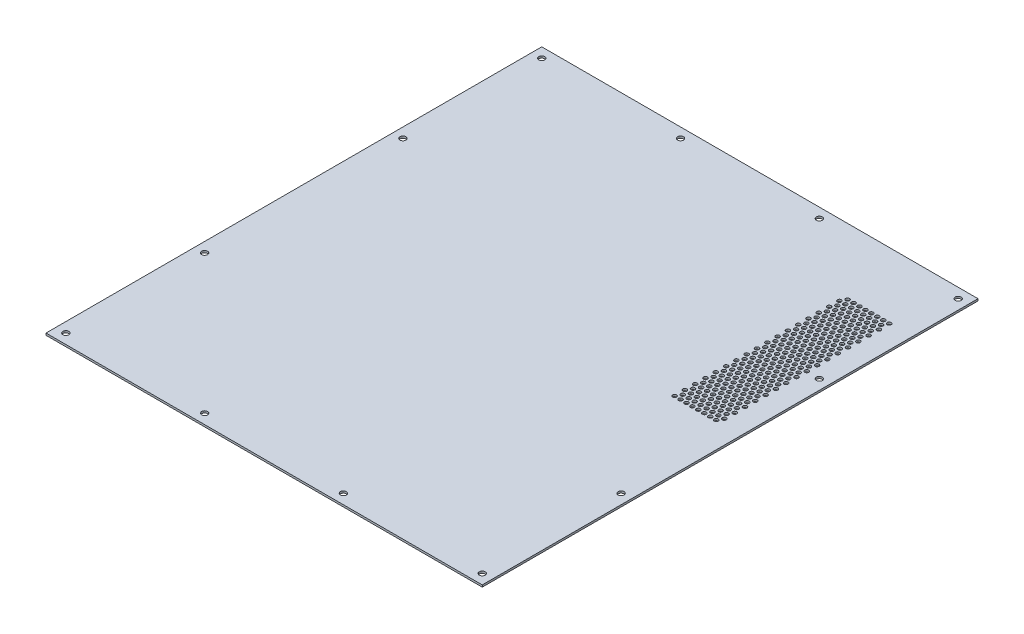
SolidWorks part; units mm, degrees
ref_plane "Front Plane" through (0, 0, 0) normal (0, 0, 1) x (1, 0, 0)
ref_plane "Top Plane" through (0, 0, 0) normal (0, 1, 0) x (1, 0, 0)
ref_plane "Right Plane" through (0, 0, 0) normal (1, 0, 0) x (0, 0, -1)
sketch "Sketch1" plane through (0, 0, 0) normal (0, 1, 0) x (1, 0, 0)
  line L0 (20, 20) -> (20, 480) construction
  line L1 (0, 0) -> (440, 0)
  line L2 (0, 0) -> (0, 500)
  line L3 (0, 500) -> (440, 500)
  line L4 (440, 0) -> (440, 500)
  line L5 (20, 480) -> (420, 480) construction
  line L6 (420, 20) -> (420, 480) construction
  line L7 (20, 20) -> (420, 20) construction
  line L9 (420, 440) -> (370, 440) construction
  line L10 (420, 440) -> (420, 260) construction
  line L11 (420, 260) -> (370, 260) construction
  line L12 (370, 440) -> (370, 260) construction
  circle A0 centre (372, 262) radius 2
  circle A1 centre (375, 267.1962) radius 2
  circle A2 centre (381, 267.1962) radius 2
  circle A3 centre (378, 262) radius 2
  circle A4 centre (387, 267.1962) radius 2
  circle A5 centre (384, 262) radius 2
  circle A6 centre (393, 267.1962) radius 2
  circle A7 centre (390, 262) radius 2
  circle A8 centre (399, 267.1962) radius 2
  circle A9 centre (396, 262) radius 2
  circle A10 centre (405, 267.1962) radius 2
  circle A11 centre (402, 262) radius 2
  circle A12 centre (411, 267.1962) radius 2
  circle A13 centre (408, 262) radius 2
  circle A14 centre (417, 267.1962) radius 2
  circle A15 centre (414, 262) radius 2
  circle A16 centre (381, 277.5862) radius 2
  circle A17 centre (378, 272.39) radius 2
  circle A18 centre (387, 277.5862) radius 2
  circle A19 centre (384, 272.39) radius 2
  circle A20 centre (393, 277.5862) radius 2
  circle A21 centre (390, 272.39) radius 2
  circle A22 centre (399, 277.5862) radius 2
  circle A23 centre (396, 272.39) radius 2
  circle A24 centre (405, 277.5862) radius 2
  circle A25 centre (402, 272.39) radius 2
  circle A26 centre (411, 277.5862) radius 2
  circle A27 centre (408, 272.39) radius 2
  circle A28 centre (417, 277.5862) radius 2
  circle A29 centre (414, 272.39) radius 2
  circle A30 centre (381, 287.9762) radius 2
  circle A31 centre (378, 282.78) radius 2
  circle A32 centre (387, 287.9762) radius 2
  circle A33 centre (384, 282.78) radius 2
  circle A34 centre (393, 287.9762) radius 2
  circle A35 centre (390, 282.78) radius 2
  circle A36 centre (399, 287.9762) radius 2
  circle A37 centre (396, 282.78) radius 2
  circle A38 centre (405, 287.9762) radius 2
  circle A39 centre (402, 282.78) radius 2
  circle A40 centre (411, 287.9762) radius 2
  circle A41 centre (408, 282.78) radius 2
  circle A42 centre (417, 287.9762) radius 2
  circle A43 centre (414, 282.78) radius 2
  circle A44 centre (381, 298.3662) radius 2
  circle A45 centre (378, 293.17) radius 2
  circle A46 centre (387, 298.3662) radius 2
  circle A47 centre (384, 293.17) radius 2
  circle A48 centre (393, 298.3662) radius 2
  circle A49 centre (390, 293.17) radius 2
  circle A50 centre (399, 298.3662) radius 2
  circle A51 centre (396, 293.17) radius 2
  circle A52 centre (405, 298.3662) radius 2
  circle A53 centre (402, 293.17) radius 2
  circle A54 centre (411, 298.3662) radius 2
  circle A55 centre (408, 293.17) radius 2
  circle A56 centre (417, 298.3662) radius 2
  circle A57 centre (414, 293.17) radius 2
  circle A58 centre (381, 308.7562) radius 2
  circle A59 centre (378, 303.56) radius 2
  circle A60 centre (387, 308.7562) radius 2
  circle A61 centre (384, 303.56) radius 2
  circle A62 centre (393, 308.7562) radius 2
  circle A63 centre (390, 303.56) radius 2
  circle A64 centre (399, 308.7562) radius 2
  circle A65 centre (396, 303.56) radius 2
  circle A66 centre (405, 308.7562) radius 2
  circle A67 centre (402, 303.56) radius 2
  circle A68 centre (411, 308.7562) radius 2
  circle A69 centre (408, 303.56) radius 2
  circle A70 centre (417, 308.7562) radius 2
  circle A71 centre (414, 303.56) radius 2
  circle A72 centre (381, 319.1462) radius 2
  circle A73 centre (378, 313.95) radius 2
  circle A74 centre (387, 319.1462) radius 2
  circle A75 centre (384, 313.95) radius 2
  circle A76 centre (393, 319.1462) radius 2
  circle A77 centre (390, 313.95) radius 2
  circle A78 centre (399, 319.1462) radius 2
  circle A79 centre (396, 313.95) radius 2
  circle A80 centre (405, 319.1462) radius 2
  circle A81 centre (402, 313.95) radius 2
  circle A82 centre (411, 319.1462) radius 2
  circle A83 centre (408, 313.95) radius 2
  circle A84 centre (417, 319.1462) radius 2
  circle A85 centre (414, 313.95) radius 2
  circle A86 centre (381, 329.5362) radius 2
  circle A87 centre (378, 324.34) radius 2
  circle A88 centre (387, 329.5362) radius 2
  circle A89 centre (384, 324.34) radius 2
  circle A90 centre (393, 329.5362) radius 2
  circle A91 centre (390, 324.34) radius 2
  circle A92 centre (399, 329.5362) radius 2
  circle A93 centre (396, 324.34) radius 2
  circle A94 centre (405, 329.5362) radius 2
  circle A95 centre (402, 324.34) radius 2
  circle A96 centre (411, 329.5362) radius 2
  circle A97 centre (408, 324.34) radius 2
  circle A98 centre (417, 329.5362) radius 2
  circle A99 centre (414, 324.34) radius 2
  circle A100 centre (381, 339.9262) radius 2
  circle A101 centre (378, 334.73) radius 2
  circle A102 centre (387, 339.9262) radius 2
  circle A103 centre (384, 334.73) radius 2
  circle A104 centre (393, 339.9262) radius 2
  circle A105 centre (390, 334.73) radius 2
  circle A106 centre (399, 339.9262) radius 2
  circle A107 centre (396, 334.73) radius 2
  circle A108 centre (405, 339.9262) radius 2
  circle A109 centre (402, 334.73) radius 2
  circle A110 centre (411, 339.9262) radius 2
  circle A111 centre (408, 334.73) radius 2
  circle A112 centre (417, 339.9262) radius 2
  circle A113 centre (414, 334.73) radius 2
  circle A114 centre (381, 350.3162) radius 2
  circle A115 centre (378, 345.12) radius 2
  circle A116 centre (387, 350.3162) radius 2
  circle A117 centre (384, 345.12) radius 2
  circle A118 centre (393, 350.3162) radius 2
  circle A119 centre (390, 345.12) radius 2
  circle A120 centre (399, 350.3162) radius 2
  circle A121 centre (396, 345.12) radius 2
  circle A122 centre (405, 350.3162) radius 2
  circle A123 centre (402, 345.12) radius 2
  circle A124 centre (411, 350.3162) radius 2
  circle A125 centre (408, 345.12) radius 2
  circle A126 centre (417, 350.3162) radius 2
  circle A127 centre (414, 345.12) radius 2
  circle A128 centre (381, 360.7062) radius 2
  circle A129 centre (378, 355.51) radius 2
  circle A130 centre (387, 360.7062) radius 2
  circle A131 centre (384, 355.51) radius 2
  circle A132 centre (393, 360.7062) radius 2
  circle A133 centre (390, 355.51) radius 2
  circle A134 centre (399, 360.7062) radius 2
  circle A135 centre (396, 355.51) radius 2
  circle A136 centre (405, 360.7062) radius 2
  circle A137 centre (402, 355.51) radius 2
  circle A138 centre (411, 360.7062) radius 2
  circle A139 centre (408, 355.51) radius 2
  circle A140 centre (417, 360.7062) radius 2
  circle A141 centre (414, 355.51) radius 2
  circle A142 centre (381, 371.0962) radius 2
  circle A143 centre (378, 365.9) radius 2
  circle A144 centre (387, 371.0962) radius 2
  circle A145 centre (384, 365.9) radius 2
  circle A146 centre (393, 371.0962) radius 2
  circle A147 centre (390, 365.9) radius 2
  circle A148 centre (399, 371.0962) radius 2
  circle A149 centre (396, 365.9) radius 2
  circle A150 centre (405, 371.0962) radius 2
  circle A151 centre (402, 365.9) radius 2
  circle A152 centre (411, 371.0962) radius 2
  circle A153 centre (408, 365.9) radius 2
  circle A154 centre (417, 371.0962) radius 2
  circle A155 centre (414, 365.9) radius 2
  circle A156 centre (381, 381.4862) radius 2
  circle A157 centre (378, 376.29) radius 2
  circle A158 centre (387, 381.4862) radius 2
  circle A159 centre (384, 376.29) radius 2
  circle A160 centre (393, 381.4862) radius 2
  circle A161 centre (390, 376.29) radius 2
  circle A162 centre (399, 381.4862) radius 2
  circle A163 centre (396, 376.29) radius 2
  circle A164 centre (405, 381.4862) radius 2
  circle A165 centre (402, 376.29) radius 2
  circle A166 centre (411, 381.4862) radius 2
  circle A167 centre (408, 376.29) radius 2
  circle A168 centre (417, 381.4862) radius 2
  circle A169 centre (414, 376.29) radius 2
  circle A170 centre (381, 391.8762) radius 2
  circle A171 centre (378, 386.68) radius 2
  circle A172 centre (387, 391.8762) radius 2
  circle A173 centre (384, 386.68) radius 2
  circle A174 centre (393, 391.8762) radius 2
  circle A175 centre (390, 386.68) radius 2
  circle A176 centre (399, 391.8762) radius 2
  circle A177 centre (396, 386.68) radius 2
  circle A178 centre (405, 391.8762) radius 2
  circle A179 centre (402, 386.68) radius 2
  circle A180 centre (411, 391.8762) radius 2
  circle A181 centre (408, 386.68) radius 2
  circle A182 centre (417, 391.8762) radius 2
  circle A183 centre (414, 386.68) radius 2
  circle A184 centre (381, 402.2662) radius 2
  circle A185 centre (378, 397.07) radius 2
  circle A186 centre (387, 402.2662) radius 2
  circle A187 centre (384, 397.07) radius 2
  circle A188 centre (393, 402.2662) radius 2
  circle A189 centre (390, 397.07) radius 2
  circle A190 centre (399, 402.2662) radius 2
  circle A191 centre (396, 397.07) radius 2
  circle A192 centre (405, 402.2662) radius 2
  circle A193 centre (402, 397.07) radius 2
  circle A194 centre (411, 402.2662) radius 2
  circle A195 centre (408, 397.07) radius 2
  circle A196 centre (417, 402.2662) radius 2
  circle A197 centre (414, 397.07) radius 2
  circle A198 centre (381, 412.6562) radius 2
  circle A199 centre (378, 407.46) radius 2
  circle A200 centre (387, 412.6562) radius 2
  circle A201 centre (384, 407.46) radius 2
  circle A202 centre (393, 412.6562) radius 2
  circle A203 centre (390, 407.46) radius 2
  circle A204 centre (399, 412.6562) radius 2
  circle A205 centre (396, 407.46) radius 2
  circle A206 centre (405, 412.6562) radius 2
  circle A207 centre (402, 407.46) radius 2
  circle A208 centre (411, 412.6562) radius 2
  circle A209 centre (408, 407.46) radius 2
  circle A210 centre (417, 412.6562) radius 2
  circle A211 centre (414, 407.46) radius 2
  circle A212 centre (381, 423.0462) radius 2
  circle A213 centre (378, 417.85) radius 2
  circle A214 centre (387, 423.0462) radius 2
  circle A215 centre (384, 417.85) radius 2
  circle A216 centre (393, 423.0462) radius 2
  circle A217 centre (390, 417.85) radius 2
  circle A218 centre (399, 423.0462) radius 2
  circle A219 centre (396, 417.85) radius 2
  circle A220 centre (405, 423.0462) radius 2
  circle A221 centre (402, 417.85) radius 2
  circle A222 centre (411, 423.0462) radius 2
  circle A223 centre (408, 417.85) radius 2
  circle A224 centre (417, 423.0462) radius 2
  circle A225 centre (414, 417.85) radius 2
  circle A226 centre (381, 433.4362) radius 2
  circle A227 centre (378, 428.24) radius 2
  circle A228 centre (387, 433.4362) radius 2
  circle A229 centre (384, 428.24) radius 2
  circle A230 centre (393, 433.4362) radius 2
  circle A231 centre (390, 428.24) radius 2
  circle A232 centre (399, 433.4362) radius 2
  circle A233 centre (396, 428.24) radius 2
  circle A234 centre (405, 433.4362) radius 2
  circle A235 centre (402, 428.24) radius 2
  circle A236 centre (411, 433.4362) radius 2
  circle A237 centre (408, 428.24) radius 2
  circle A238 centre (417, 433.4362) radius 2
  circle A239 centre (414, 428.24) radius 2
  circle A240 centre (375, 277.5862) radius 2
  circle A241 centre (372, 272.39) radius 2
  circle A242 centre (375, 287.9762) radius 2
  circle A243 centre (372, 282.78) radius 2
  circle A244 centre (375, 298.3662) radius 2
  circle A245 centre (372, 293.17) radius 2
  circle A246 centre (375, 308.7562) radius 2
  circle A247 centre (372, 303.56) radius 2
  circle A248 centre (375, 319.1462) radius 2
  circle A249 centre (372, 313.95) radius 2
  circle A250 centre (375, 329.5362) radius 2
  circle A251 centre (372, 324.34) radius 2
  circle A252 centre (375, 339.9262) radius 2
  circle A253 centre (372, 334.73) radius 2
  circle A254 centre (375, 350.3162) radius 2
  circle A255 centre (372, 345.12) radius 2
  circle A256 centre (375, 360.7062) radius 2
  circle A257 centre (372, 355.51) radius 2
  circle A258 centre (375, 371.0962) radius 2
  circle A259 centre (372, 365.9) radius 2
  circle A260 centre (375, 381.4862) radius 2
  circle A261 centre (372, 376.29) radius 2
  circle A262 centre (375, 391.8762) radius 2
  circle A263 centre (372, 386.68) radius 2
  circle A264 centre (375, 402.2662) radius 2
  circle A265 centre (372, 397.07) radius 2
  circle A266 centre (375, 412.6562) radius 2
  circle A267 centre (372, 407.46) radius 2
  circle A268 centre (375, 423.0462) radius 2
  circle A269 centre (372, 417.85) radius 2
  circle A270 centre (375, 433.4362) radius 2
  circle A271 centre (372, 428.24) radius 2
  circle A272 centre (10, 490) radius 3
  circle A273 centre (430, 490) radius 3
  circle A274 centre (430, 10) radius 3
  circle A275 centre (10, 10) radius 3
  circle A276 centre (430, 150) radius 3
  circle A277 centre (430, 350) radius 3
  circle A278 centre (10, 150) radius 3
  circle A279 centre (10, 350) radius 3
  circle A280 centre (150, 10) radius 3
  circle A281 centre (290, 10) radius 3
  circle A282 centre (150, 490) radius 3
  circle A283 centre (290, 490) radius 3
  dimension "D7" = 2
  dimension "D8" = 2
  dimension "D12" = 10
  dimension "D14" = 10
  dimension "D21" = 6
  dimension "D22" = 4
  dimension "D2" = 180
  dimension "D3" = 50
  dimension "D4" = 60
  dimension "D5" = 500
  dimension "D6" = 440
  dimension "D9" = 8
  dimension "D10" = 17
  dimension "D11" = 6
  dimension "D13" = 5.1962
  dimension "D15" = 10
  dimension "D16" = 10
  dimension "D17" = 10
  dimension "D18" = 10
  dimension "D19" = 10
  dimension "D20" = 10
  dimension "D23" = 150
  dimension "D24" = 350
  dimension "D25" = 150
  dimension "D26" = 150
  dimension "D27" = 350
  dimension "D28" = 150
  dimension "D29" = 150
  dimension "D30" = 150
  dimension "D31" = 150
  dimension "D32" = 150
  dimension "D1" = 20
extrude "Boss-Extrude1" add sketch "Sketch1" along normal blind 2
